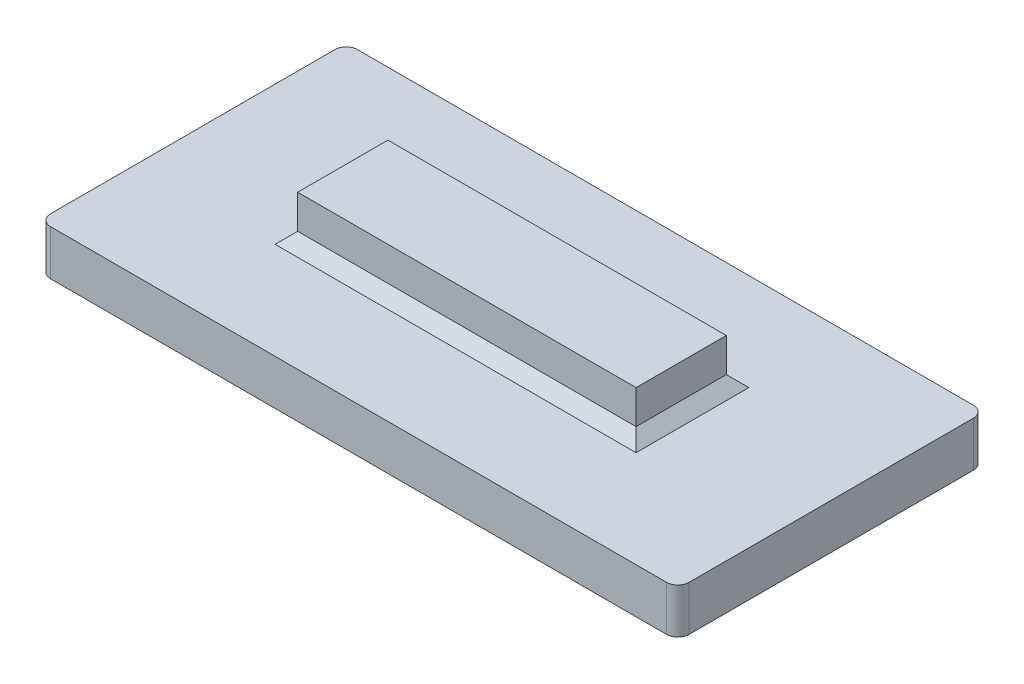
SolidWorks part; units mm, degrees
ref_plane "Front Plane" through (0, 0, 0) normal (0, 0, 1) x (1, 0, 0)
ref_plane "Top Plane" through (0, 0, 0) normal (0, 1, 0) x (1, 0, 0)
ref_plane "Right Plane" through (0, 0, 0) normal (1, 0, 0) x (0, 0, -1)
sketch "Sketch1" plane through (0, 0, 0) normal (0, 1, 0) x (1, 0, 0)
  line L1 (-14.15, -6.8) -> (14.15, -6.8)
  line L2 (-14.15, -6.8) -> (-14.15, 6.8)
  line L3 (-14.15, 6.8) -> (14.15, 6.8)
  line L4 (14.15, -6.8) -> (14.15, 6.8)
  line L5 (-14.15, -6.8) -> (14.15, 6.8) construction
  line L6 (-14.15, 6.8) -> (14.15, -6.8) construction
  point P0 (0, 0)
  dimension "D1" = 28.3
  dimension "D2" = 13.6
extrude "Boss-Extrude1" add sketch "Sketch1" along normal blind 2 contours L3 L4 L1 L2
fillet "Fillet1" radius 0.5 4 edges at (14.15, 1, 6.8) (-14.15, 1, 6.8) (-14.15, 1, -6.8) (14.15, 1, -6.8)
sketch "Sketch2" plane through (0, 2, 0) normal (0, 1, 0) x (1, 0, 0)
  line L1 (-7.5, -2) -> (7.5, -2)
  line L2 (-7.5, -2) -> (-7.5, 2)
  line L3 (-7.5, 2) -> (7.5, 2)
  line L4 (7.5, -2) -> (7.5, 2)
  line L5 (-7.5, -2) -> (7.5, 2) construction
  line L6 (-7.5, 2) -> (7.5, -2) construction
  point P0 (0, 0)
  dimension "D1" = 4
  dimension "D2" = 15
extrude "Boss-Extrude2" add sketch "Sketch2" along normal blind 2
chamfer "Chamfer1" distance 0.5 angle 45 4 edges at (-7.5, 2, 0) (0, 2, 2) (7.5, 2, 0) (0, 2, -2)
